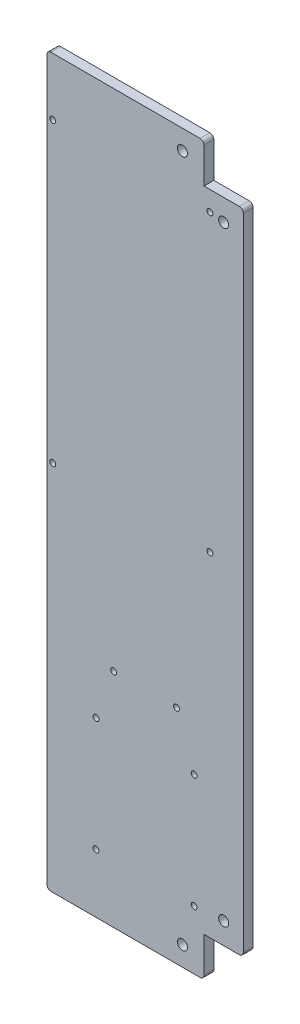
SolidWorks part; units mm, degrees
ref_plane "前视基准面" through (0, 0, 0) normal (0, 0, 1) x (1, 0, 0)
ref_plane "上视基准面" through (0, 0, 0) normal (0, 1, 0) x (1, 0, 0)
ref_plane "右视基准面" through (0, 0, 0) normal (1, 0, 0) x (0, 0, -1)
sketch "草图2" plane through (0, 0, 0) normal (0, 0, 1) x (1, 0, 0)
  line L1 (50, -185) -> (-50, -185)
  line L2 (50, -185) -> (50, 185)
  line L3 (50, 185) -> (-50, 185)
  line L4 (-50, -185) -> (-50, 185)
  line L5 (50, -185) -> (-50, 185) construction
  line L6 (50, 185) -> (-50, -185) construction
  point P0 (0, 0)
  dimension "D1" = 370
  dimension "D2" = 100
extrude "凸台-拉伸1" add sketch "草图2" along normal mid plane 5
sketch "草图5" plane through (0, 0, 2.5) normal (0, 0, 1) x (1, 0, 0)
  line L0 (0, 80) -> (0, 66.4415) construction
  line L2 (-7, 155) -> (33, 155) construction
  line L3 (0, 80) -> (18.6102, 80) construction
  line L4 (-50, 185) -> (-50, -185) construction
  line L5 (50, 185) -> (-50, 185) construction
  line L7 (-7, 155) -> (-7, 80) construction
  circle A0 centre (33, 155) radius 1.5
  circle A1 centre (-47, 155.6548) radius 1.5
  circle A4 centre (33, 5) radius 1.5
  circle A5 centre (-47, 4.3452) radius 1.5
  point P18 (0, 0)
  dimension "D1" = 3
  dimension "D5" = 3
  dimension "D7" = 3
  dimension "D2" = 40
  dimension "D3" = 75
  dimension "D4" = 30
  dimension "D6" = 80
extrude "切除-拉伸3" cut sketch "草图5" against normal through all
sketch "草图6" plane through (0, 0, 2.5) normal (0, 0, 1) x (1, 0, 0)
  line L0 (0, -126) -> (0, -155) construction
  line L1 (0, -126) -> (29.0518, -126) construction
  line L2 (0, -155) -> (25, -155) construction
  line L3 (-50, -185) -> (50, -185) construction
  circle A0 centre (25, -155) radius 1.5
  circle A1 centre (-25, -155) radius 1.5
  circle A2 centre (25, -97) radius 1.5
  circle A3 centre (-25, -97) radius 1.5
  dimension "D1" = 3
  dimension "D2" = 25
  dimension "D3" = 29
  dimension "D4" = 30
extrude "切除-拉伸4" cut sketch "草图6" against normal through all
sketch "草图7" plane through (0, 0, 2.5) normal (0, 0, 1) x (1, 0, 0)
  line L0 (0, 0) -> (50, 0) construction
  line L1 (50, 185) -> (30, 185)
  line L2 (50, 185) -> (50, 165)
  line L3 (50, 165) -> (30, 165)
  line L4 (30, 185) -> (30, 165)
  line L5 (50, -185) -> (50, 185) construction
  line L6 (0, 0) -> (0, 36.2531) construction
  line L7 (30, -185) -> (30, -165)
  line L8 (50, -165) -> (30, -165)
  line L9 (50, -185) -> (50, -165)
  line L10 (50, -185) -> (30, -185)
  line L11 (-50, -185) -> (-30, -185)
  line L12 (-50, -185) -> (-50, -165)
  line L13 (-50, -165) -> (-30, -165)
  line L14 (-30, -185) -> (-30, -165)
  line L15 (-30, 185) -> (-30, 165)
  line L16 (-50, 165) -> (-30, 165)
  line L17 (-50, 185) -> (-50, 165)
  line L18 (-50, 185) -> (-30, 185)
  line L19 (50, 185) -> (-50, 185) construction
  dimension "D1" = 20
  dimension "D2" = 20
extrude "切除-拉伸5" cut sketch "草图7" against normal through all contours L2 L1 L4 L3 | L7 L8 L9 L10
sketch "草图8" plane through (0, 0, -2.5) normal (0, 0, -1) x (-1, 0, 0)
  line L0 (-23.45, 175) -> (-14.55, 175) construction
  line L1 (-40, 158.45) -> (-40, 149.55) construction
  line L2 (-40, -149.55) -> (-40, -158.45) construction
  line L3 (-14.55, -175) -> (-23.45, -175) construction
  arc A0 (-17.5, 172.05) -> (-17.5, 177.95) centre (-17.5, 175) ccw construction
  arc A1 (-42.95, 152.5) -> (-37.05, 152.5) centre (-40, 152.5) ccw construction
  arc A2 (-37.05, -152.5) -> (-42.95, -152.5) centre (-40, -152.5) ccw construction
  arc A3 (-42.95, -155.5) -> (-37.05, -155.5) centre (-40, -155.5) ccw construction
  arc A4 (-17.5, -177.95) -> (-17.5, -172.05) centre (-17.5, -175) ccw construction
  arc A5 (-20.5, -172.05) -> (-20.5, -177.95) centre (-20.5, -175) ccw construction
  circle A6 centre (-19, 175) radius 2.55
  circle A7 centre (-40, 154) radius 2.55
  circle A8 centre (-40, -154) radius 2.55
  circle A9 centre (-19, -175) radius 2.55
  dimension "D1" = 5.1
extrude "切除-拉伸6" cut sketch "草图8" against normal through all
fillet "圆角1" radius 2 6 edges at (30, -185, 0) (50, -165, 0) (50, 165, 0) (30, 185, 0) (-50, -185, 0) (-50, 185, 0)
sketch "草图10" plane through (0, 0, -2.5) normal (0, 0, -1) x (-1, 0, 0)
  line L0 (0, 0) -> (0, -179.4404) construction
  line L1 (-25, -97) -> (0, -97) construction
  line L2 (0, -72) -> (0, -47)
  circle A0 centre (-16, -72) radius 1.5
  circle A1 centre (16, -72) radius 1.5
  dimension "D1" = 25
  dimension "D2" = 3
  dimension "D3" = 16
  dimension "D4" = 25
extrude "切除-拉伸7" cut sketch "草图10" against normal blind 13 contours A0 | A1
